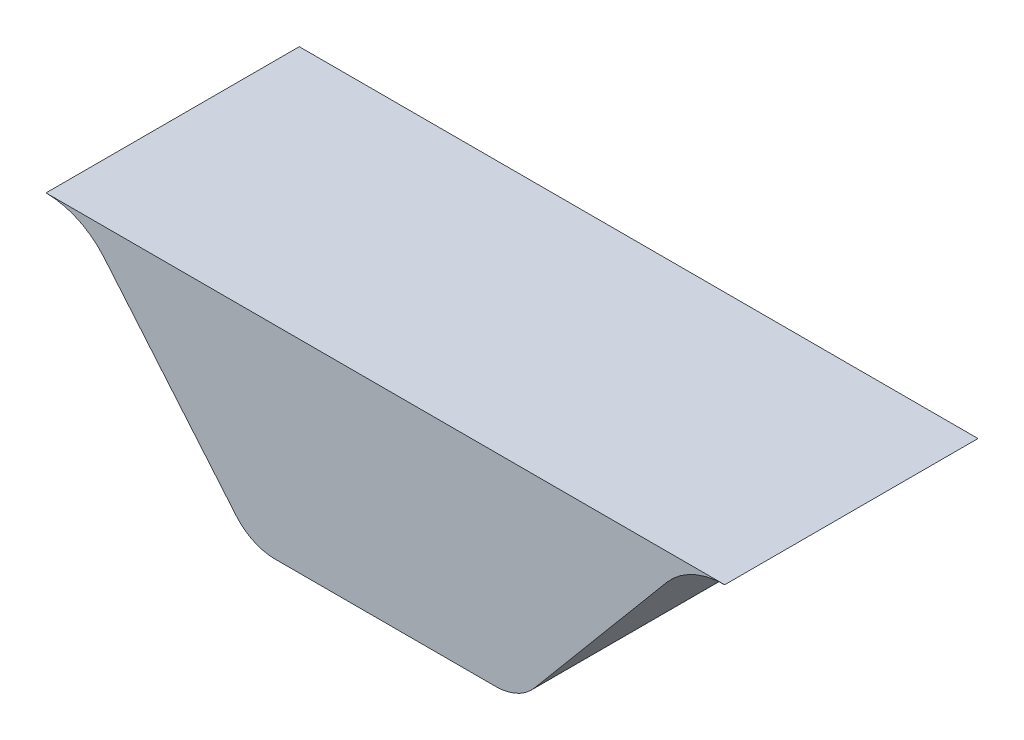
SolidWorks part; units mm, degrees
ref_plane "Front Plane" through (0, 0, 0) normal (0, 0, 1) x (1, 0, 0)
ref_plane "Top Plane" through (0, 0, 0) normal (0, 1, 0) x (1, 0, 0)
ref_plane "Right Plane" through (0, 0, 0) normal (1, 0, 0) x (0, 0, -1)
sketch "Sketch1" plane through (0, 0, 0) normal (0, 0, 1) x (1, 0, 0)
  line L1 (-25, 0) -> (25, 0)
  line L2 (-25, 0) -> (-25, 5)
  line L3 (-25, 5) -> (25, 5)
  line L4 (25, 0) -> (25, 5)
  dimension "D1" = 50
  dimension "D2" = 5
extrude "Boss-Extrude1" add sketch "Sketch1" along normal mid plane 50
sketch "Sketch2" plane through (0, 0, 0) normal (0, 0, 1) x (1, 0, 0)
  line L0 (-6, 0) -> (6, 0)
  line L1 (-25, 0) -> (25, 0) construction
  line L2 (6, 0) -> (2.6436, -4)
  line L3 (2.6436, -4) -> (-2.6436, -4)
  line L4 (-2.6436, -4) -> (-6, 0)
  dimension "D1" = 12
  dimension "D2" = 4
  dimension "D3" = 50
extrude "Boss-Extrude2" add sketch "Sketch2" along normal mid plane 5
fillet "Fillet1" radius 1 2 edges at (-2.6436, -4, 0) (2.6436, -4, 0)
fillet "Fillet2" radius 1.5 2 edges at (-6, 0, 0) (6, 0, 0)
sketch "Sketch3" plane through (0, -4, 0) normal (0, -1, 0) x (1, 0, 0)
  circle A0 centre (0, 0) radius 1.5
  dimension "D1" = 3
split line "Split Line1"
sketch "Sketch4" plane through (0, 0, 25) normal (0, 0, 1) x (1, 0, 0)
  line L4 (-25, 5) -> (-25, 0)
  line L5 (-25, 0) -> (25, 0)
  line L6 (25, 0) -> (25, 5)
  line L7 (25, 5) -> (-25, 5)
  line L8 (-25, 5) -> (-25, 0)
  line L9 (-25, 0) -> (25, 0)
  line L10 (25, 0) -> (25, 5)
  line L11 (25, 5) -> (-25, 5)
  dimension "D1" = 0
extrude "Cut-Extrude1" cut sketch "Sketch4" against normal through all
sketch "Orientation Sketch" plane through (0, 0, 0) normal (0, 1, 0) x (1, 0, 0)
  line L0 (6.6995, -2.5) -> (-6.6995, -2.5) construction
  line L1 (6.6995, -2.5) -> (6.6995, 2.5) construction
  line L2 (6.6995, 2.5) -> (-6.6995, 2.5) construction
  line L3 (-6.6995, 2.5) -> (-6.6995, -2.5) construction
  line L4 (6.6995, -2.5) -> (-6.6995, -2.5)
  line L5 (6.6995, -2.5) -> (6.6995, 2.5)
  line L6 (6.6995, 2.5) -> (-6.6995, 2.5)
  line L7 (-6.6995, 2.5) -> (-6.6995, -2.5)
  point P2 (0, 0)
other "FormTool1"
